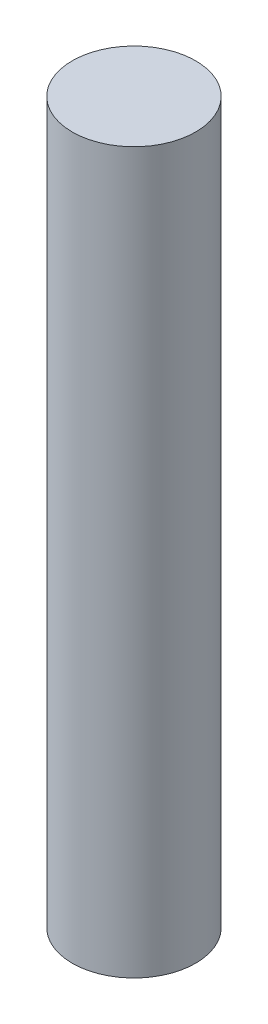
SolidWorks part; units mm, degrees
material "ABS"
ref_plane "Alzado" through (0, 0, 0) normal (0, 0, 1) x (1, 0, 0)
ref_plane "Planta" through (0, 0, 0) normal (0, 1, 0) x (1, 0, 0)
ref_plane "Vista lateral" through (0, 0, 0) normal (1, 0, 0) x (0, 0, -1)
sketch "Croquis2" plane through (0, 0, 0) normal (0, 1, 0) x (1, 0, 0)
  circle A0 centre (0, 0) radius 2.4
  dimension "D1" = 4.8
extrude "Saliente-Extruir1" add sketch "Croquis2" along normal mid plane 28
